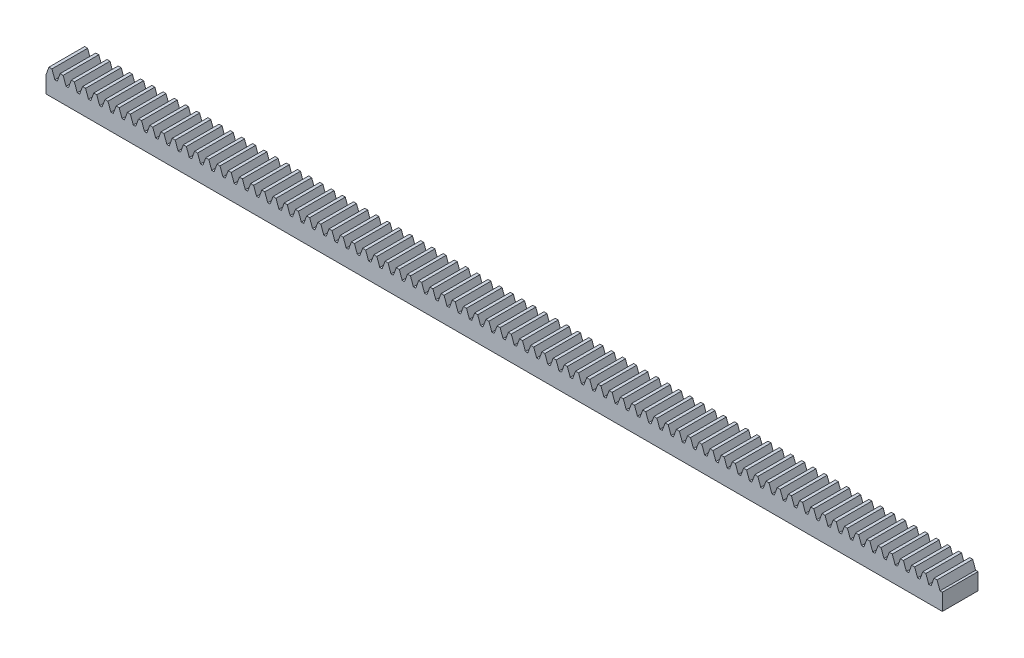
SolidWorks part; units mm, degrees
ref_plane "前视基准面" through (0, 0, 0) normal (0, 0, 1) x (1, 0, 0)
ref_plane "上视基准面" through (0, 0, 0) normal (0, 1, 0) x (1, 0, 0)
ref_plane "右视基准面" through (0, 0, 0) normal (1, 0, 0) x (0, 0, -1)
sketch "草图1" plane through (0, 0, 0) normal (0, 0, 1) x (1, 0, 0)
  line L1 (0, 0) -> (502.6548, 0)
  line L2 (0, 0) -> (0, -9.35)
  line L3 (0, -9.35) -> (502.6548, -9.35)
  line L4 (502.6548, 0) -> (502.6548, -9.35)
  dimension "D1" = 9.35
  dimension "L" = 502.6548
extrude "拉伸1" add sketch "草图1" along normal blind 20
sketch "草图2" plane through (0, 0, 20) normal (0, 0, 1) x (1, 0, 0)
  line L0 (0, 0) -> (1.6379, 4.5)
  line L1 (1.6379, 4.5) -> (3.3236, 4.5)
  line L2 (3.3236, 4.5) -> (4.9614, 0)
  line L3 (502.6548, 0) -> (0, 0) construction
  line L4 (0, 0) -> (4.9614, 0)
  line L5 (0.9099, 2.5) -> (4.0515, 2.5) construction
  dimension "D2" = 70
  dimension "alpha" = 110
  dimension "ha" = 2
  dimension "hf" = 2.5
  dimension "S" = 3.1416
extrude "拉伸2" add sketch "草图2" against normal up to surface (20 mm away) up to face at (251.3274, -4.675, 0)
pattern_linear "阵列(线性)1" count 80 spacing 6.2832 along (1, 0, 0) of "拉伸2"
equation "\"d\"=\"S@草图2\" * 2"
equation "\"z\"= int(  \"L@草图1\" / (  \"S@草图2\" * 2 ) + 0.5 )"
